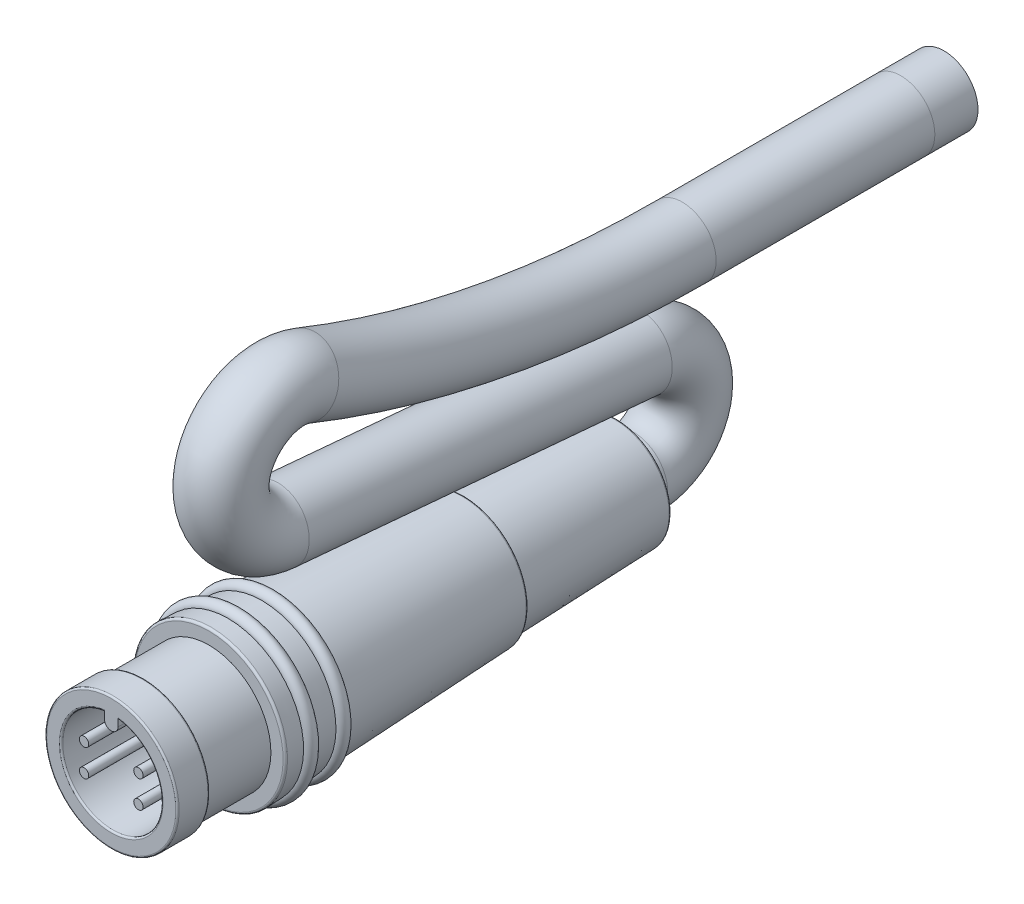
SolidWorks part; units mm, degrees
ref_plane "Front Plane" through (0, 0, 0) normal (0, 0, 1) x (1, 0, 0)
ref_plane "Top Plane" through (0, 0, 0) normal (0, 1, 0) x (1, 0, 0)
ref_plane "Right Plane" through (0, 0, 0) normal (1, 0, 0) x (0, 0, -1)
sketch "Sketch1" plane through (0, 0, 0) normal (1, 0, 0) x (0, 0, -1)
  line L0 (0, 0) -> (0, 4.3669)
  line L1 (0.1329, 4.4938) -> (14.8789, 3.803)
  line L2 (15, 3.6761) -> (15, 3.6532)
  line L3 (15.1225, 3.5263) -> (23.8775, 3.2174)
  line L4 (24, 3.0905) -> (24, 0)
  line L5 (24, 0) -> (0, 0)
  line L6 (-5.65, 2.95) -> (0, 2.95)
  line L8 (0, 3.65) -> (-3.75, 3.65)
  line L9 (-5.75, 3.8) -> (-5.75, 3.05)
  line L11 (24, 2) -> (49, 2)
  line L12 (49, 2) -> (49, 0)
  line L13 (49, 0) -> (24, 0)
  line L14 (-5.65, 3.9) -> (-3.95, 3.9)
  line L15 (-3.85, 3.8) -> (-3.85, 3.75)
  arc A0 (23.8775, 3.2174) -> (24, 3.0905) centre (23.873, 3.0905) cw
  arc A1 (15, 3.6532) -> (15.1225, 3.5263) centre (15.127, 3.6532) ccw
  arc A2 (14.8789, 3.803) -> (15, 3.6761) centre (14.873, 3.6761) cw
  arc A3 (0, 4.3669) -> (0.1329, 4.4938) centre (0.127, 4.3669) cw
  circle A4 centre (1.5, 4.4297) radius 0.375
  circle A5 centre (3.5, 4.336) radius 0.375
  arc A13 (-3.75, 3.65) -> (-3.85, 3.75) centre (-3.75, 3.75) cw
  arc A14 (-3.95, 3.9) -> (-3.85, 3.8) centre (-3.95, 3.8) cw
  arc A15 (-5.75, 3.8) -> (-5.65, 3.9) centre (-5.65, 3.8) cw
  arc A16 (-5.65, 2.95) -> (-5.75, 3.05) centre (-5.65, 3.05) cw
  point P9 (24, 3.2131)
  point P12 (15, 3.5306)
  point P15 (15, 3.7973)
  point P18 (0, 4.5)
  dimension "D7" = 0.127
  dimension "D12" = 0.75
  dimension "D8" = 0.1
  dimension "D16" = 0.1
  dimension "D1" = 3.7973
  dimension "D2" = 4.5
  dimension "D3" = 15
  dimension "D4" = 3.5306
  dimension "D5" = 3.2131
  dimension "D6" = 24
  dimension "D9" = 2.95
  dimension "D10" = 5.75
  dimension "D11" = 3.9
  dimension "D13" = 1.5
  dimension "D14" = 3.5
  dimension "D15" = 3.65
  dimension "D17" = 1.9
  dimension "D19" = 2
  dimension "D20" = 25
revolve "Revolve1" add sketch "Sketch1" angle 360 about L5
sketch "Sketch2" plane through (0, 0, 0) normal (0, 0, 1) x (1, 0, 0)
  line L0 (0, 2.95) -> (0, 2.55) construction
  line L1 (0.4, 2.95) -> (0.4, 2.55)
  line L2 (-0.4, 2.95) -> (-0.4, 2.55)
  line L3 (-1.6, 0.8) -> (-1.6, -0.8) construction
  line L4 (0, -5.2852) -> (0, 5.2852) construction
  arc A2 (0.4, 2.95) -> (-0.4, 2.95) centre (0, 2.95) ccw
  arc A3 (-0.4, 2.55) -> (0.4, 2.55) centre (0, 2.55) ccw
  circle A4 centre (-1.6, 0.8) radius 0.275
  circle A5 centre (-1.6, -0.8) radius 0.275
  circle A6 centre (1.6, -0.8) radius 0.275
  circle A7 centre (1.6, 0.8) radius 0.275
  circle A8 centre (0, 0) radius 2.95 construction
  point P7 (0, 2.75)
  point P14 (-1.6, 0)
  dimension "D2" = 0.55
  dimension "D4" = 0.4
  dimension "D1" = 1.6
  dimension "D3" = 1.6
extrude "Boss-Extrude1" add sketch "Sketch2" along normal up to surface (5.75 mm away) up to face at (0, 3.05, 5.75)
sketch "Sketch3" plane through (0, 0, 0) normal (1, 0, 0) x (0, 0, -1)
  line L2 (3.8976, 7.889) -> (25.2658, 5.9882)
  line L3 (19.1545, 22.7383) -> (20.1817, 18.9047) construction
  line L4 (40.732, 10.3066) -> (27.8581, 10.3066)
  line L5 (40.8198, 12.4148) -> (31.5245, 12.4148) construction
  line L6 (40.732, 10.3066) -> (43.272, 10.3066)
  line L8 (25, 0) -> (24, 0)
  line L9 (24, -3.0905) -> (24, 3.0905) construction
  line L10 (40.732, 8.7191) -> (40.732, 11.8941) construction
  arc A1 (25.2658, 5.9882) -> (25, 0) centre (25, 3) cw
  arc A2 (5.5113, 14.6234) -> (27.8581, 10.3066) centre (27.8581, 70.3066) ccw
  arc A3 (5.5113, 14.6234) -> (3.8976, 7.889) centre (4.2077, 11.3752) ccw
  point P7 (19.6681, 20.8215)
  dimension "D1" = 3
  dimension "D3" = 60
  dimension "D2" = 7
  dimension "D4" = 1
  dimension "D5" = 2.54
sweep "Sweep4" add path "Sketch3" circular profile diameter 4 parameters "D3"=4
